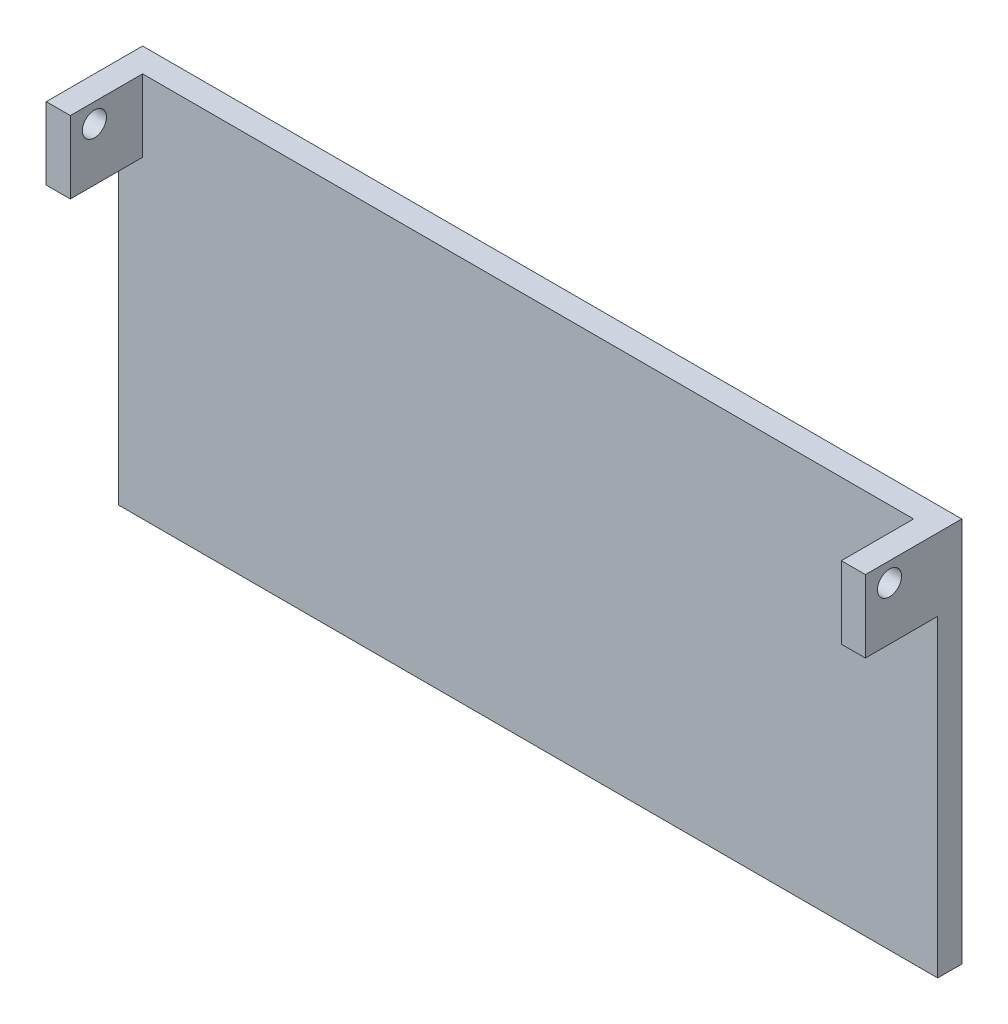
SolidWorks part; units mm, degrees
ref_plane "前视基准面" through (0, 0, 0) normal (0, 0, 1) x (1, 0, 0)
ref_plane "上视基准面" through (0, 0, 0) normal (0, 1, 0) x (1, 0, 0)
ref_plane "右视基准面" through (0, 0, 0) normal (1, 0, 0) x (0, 0, -1)
sketch "草图1" plane through (0, 0, 0) normal (0, 0, 1) x (1, 0, 0)
  line L0 (-87.9437, 0) -> (82.0563, 0) construction
  line L2 (82.0563, 0) -> (-87.9437, 0)
  line L3 (82.0563, 0) -> (82.0563, -80)
  line L4 (82.0563, -80) -> (-87.9437, -80)
  line L5 (-87.9437, 0) -> (-87.9437, -80)
  dimension "D1" = 170
  dimension "D2" = 80
extrude "凸台-拉伸1" add sketch "草图1" along normal blind 5
sketch "草图2" plane through (-87.9437, 0, 0) normal (-1, 0, 0) x (0, 0, 1)
  line L1 (0, 0) -> (20, 0)
  line L2 (0, 0) -> (0, -15)
  line L3 (0, -15) -> (20, -15)
  line L4 (20, 0) -> (20, -15)
  circle A0 centre (15, -4) radius 2.5
  dimension "D1" = 5
  dimension "D2" = 4
  dimension "D3" = 15
  dimension "D4" = 15
  dimension "D5" = 20
extrude "凸台-拉伸2" add sketch "草图2" against normal blind 5
sketch "草图3" plane through (82.0563, 0, 0) normal (1, 0, 0) x (0, 0, -1)
  line L4 (0, 0) -> (-20, 0)
  line L5 (-20, 0) -> (-20, -15)
  line L6 (-20, -15) -> (0, -15)
  line L7 (0, -15) -> (0, 0)
  line L8 (0, 0) -> (-20, 0)
  line L9 (-20, 0) -> (-20, -15)
  line L10 (-20, -15) -> (0, -15)
  line L11 (0, -15) -> (0, 0)
  circle A1 centre (-15, -4) radius 2.5
  circle A2 centre (-15, -4) radius 2.5
  dimension "D1" = 0
  dimension "D2" = 0
extrude "凸台-拉伸3" add sketch "草图3" against normal blind 5
